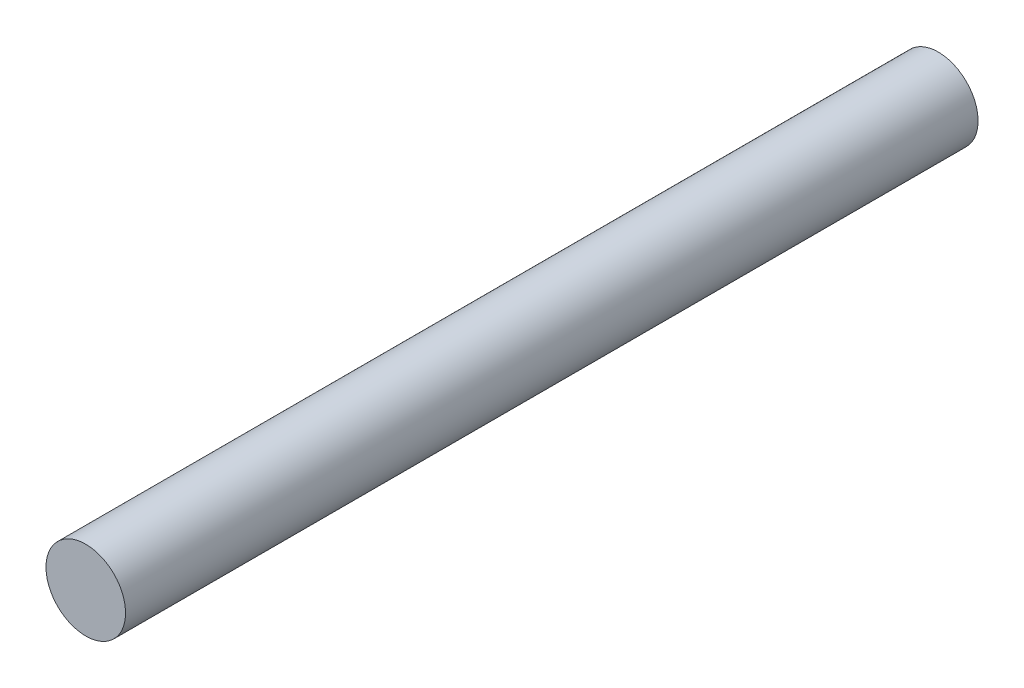
SolidWorks part; units mm, degrees
ref_plane "Front Plane" through (0, 0, 0) normal (1, 0, 0) x (0, 1, 0)
ref_plane "Top Plane" through (0, 0, 0) normal (0, 0, 1) x (0, 1, 0)
ref_plane "Right Plane" through (0, 0, 0) normal (0, 1, 0) x (-1, 0, 0)
sketch "Sketch1" plane through (0, 0, 0) normal (0, 0, 1) x (0, 1, 0)
  circle A0 centre (0, 0) radius 1.778
  dimension "D1" = 3.556
extrude "Boss-Extrude1" add sketch "Sketch1" along normal blind 38.1 contours A0
